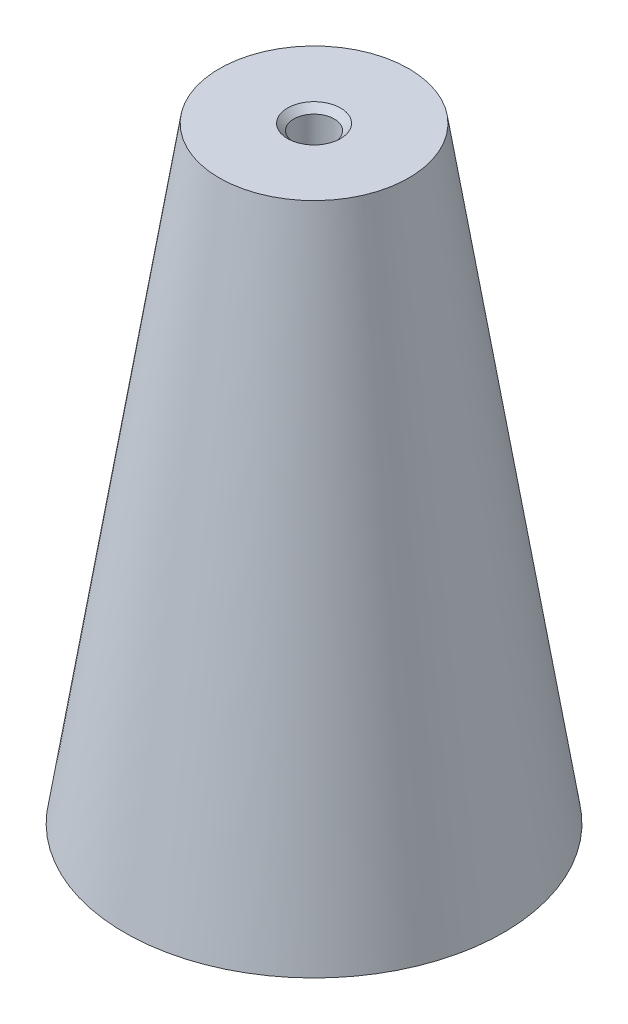
SolidWorks part; units mm, degrees
ref_plane "前视基准面" through (0, 0, 0) normal (0, 0, 1) x (1, 0, 0)
ref_plane "上视基准面" through (0, 0, 0) normal (0, 1, 0) x (1, 0, 0)
ref_plane "右视基准面" through (0, 0, 0) normal (1, 0, 0) x (0, 0, -1)
other "Configuration Table"
sketch "草图3" plane through (0, 0, 0) normal (1, 0, 0) x (0, 0, -1)
  line L0 (-7.5, 0) -> (0, 0)
  line L1 (0, 0) -> (0, -4)
  line L2 (0, -4) -> (-4.125, -4)
  line L3 (-4.125, -4) -> (-11, -48)
  line L4 (-11, -48) -> (-15, -48)
  line L5 (-15, -48) -> (-7.5, 0)
  line L6 (0, 28.4507) -> (0, 37.5487) construction
  dimension "D1" = 4
  dimension "D2" = 4
  dimension "D3" = 48
  dimension "D4" = 7.5
  dimension "D5" = 15
revolve "旋转1" add sketch "草图3" angle 360 about L6
sketch "草图4" plane through (0, 0, 0) normal (0, 1, 0) x (1, 0, 0)
  circle A0 centre (0, 0) radius 1.6
  dimension "D1" = 3.2
extrude "切除-拉伸1" cut sketch "草图4" against normal blind 10 contours A0
chamfer "倒角1" distance 0.5 angle 45 2 edges at (0, -4, 1.6) (0, 0, 1.6)
